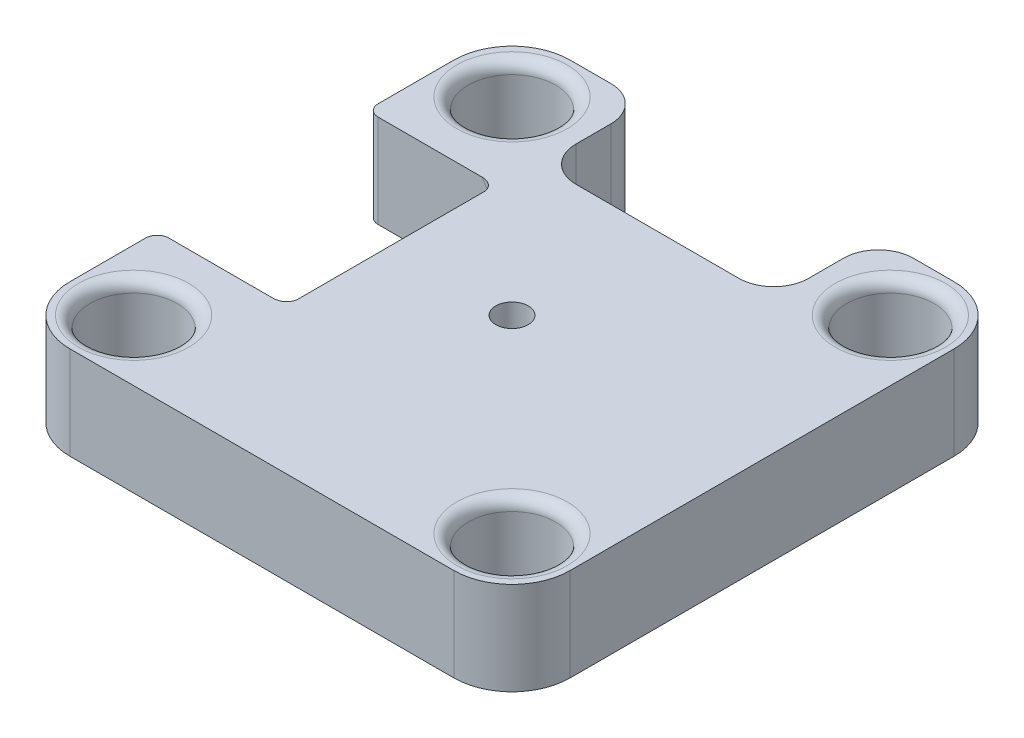
SolidWorks part; units mm, degrees
ref_plane "Front Plane" through (0, 0, 0) normal (0, 0, 1) x (1, 0, 0)
ref_plane "Top Plane" through (0, 0, 0) normal (0, 1, 0) x (1, 0, 0)
ref_plane "Right Plane" through (0, 0, 0) normal (1, 0, 0) x (0, 0, -1)
sketch "Sketch1" plane through (0, 0, 0) normal (0, 1, 0) x (1, 0, 0)
  line L0 (-20.6546, 20.6546) -> (0, 0) construction
  line L2 (27.305, -27.305) -> (-27.305, -27.305)
  line L3 (27.305, -27.305) -> (27.305, 27.305)
  line L4 (27.305, 27.305) -> (-27.305, 27.305)
  line L5 (-27.305, -27.305) -> (-27.305, 27.305)
  line L6 (27.305, -27.305) -> (-27.305, 27.305) construction
  line L7 (27.305, 27.305) -> (-27.305, -27.305) construction
  circle A0 centre (-20.6546, 20.6546) radius 4.7625
  circle A1 centre (20.6546, 20.6546) radius 4.7625
  circle A2 centre (20.6546, -20.6546) radius 4.7625
  circle A3 centre (-20.6546, -20.6546) radius 4.7625
  point P13 (0, 0)
  dimension "D3" = 9.525
  dimension "D1" = 45
  dimension "D2" = 29.21
  dimension "D5" = 54.61
  dimension "D4" = 4
extrude "Boss-Extrude1" add sketch "Sketch1" along normal mid plane 10.16
fillet "Fillet1" radius 6.35 4 edges at (-27.305, 0, -27.305) (27.305, 0, -27.305) (27.305, 0, 27.305) (-27.305, 0, 27.305)
fillet "Fillet2" radius 1.27 8 edges at (20.6546, 5.08, 25.4171) (20.6546, -5.08, 25.4171) (-20.6546, 5.08, 25.4171) (-20.6546, -5.08, 25.4171) (20.6546, -5.08, -15.8921) (20.6546, 5.08, -15.8921) (-20.6546, -5.08, -15.8921) (-20.6546, 5.08, -15.8921)
sketch "Sketch4" plane through (0, 0, 0) normal (0, 0, 1) x (1, 0, 0)
  line L0 (-27.305, 5.08) -> (-13.208, 5.08)
  line L1 (-20.955, 5.08) -> (20.955, 5.08) construction
  line L2 (-13.208, 5.08) -> (-8.128, -3.556)
  line L3 (-8.128, -3.556) -> (11.43, -3.556)
  line L4 (11.43, -3.556) -> (11.43, -5.08)
  line L5 (-20.955, -5.08) -> (20.955, -5.08) construction
  line L6 (11.43, -5.08) -> (-27.305, -5.08)
  line L7 (-27.305, -5.08) -> (-20.955, -5.08) construction
  line L8 (-27.305, -5.08) -> (-27.305, 5.08)
  dimension "D1" = 38.735
  dimension "D2" = 19.558
  dimension "D3" = 5.08
  dimension "D4" = 8.636
extrude "Cut-Extrude1" cut sketch "Sketch4" against normal mid plane 22.86
sketch "Sketch5" plane through (0, -3.556, 0) normal (0, -1, 0) x (1, 0, 0)
  line L1 (11.43, -11.43) -> (11.43, 11.43) construction
  circle A0 centre (0, 0) radius 1.778
  point P3 (11.43, 0)
  dimension "D1" = 3.556
extrude "Cut-Extrude2" cut sketch "Sketch5" against normal through all
fillet "Fillet3" radius 1.27 8 edges at (1.651, -3.556, -11.43) (1.651, -3.556, 11.43) (11.43, -3.556, 0) (-10.668, 0.762, -11.43) (-8.128, -3.556, 0) (-10.668, 0.762, 11.43) (-27.305, 0, -11.43) (-27.305, 0, 11.43)
sketch "Sketch6" plane through (0, 5.08, 0) normal (0, 1, 0) x (1, 0, 0)
  line L0 (20.955, 27.305) -> (-20.955, 27.305) construction
  line L1 (-12.7, 38.735) -> (12.7, 38.735)
  line L2 (-12.7, 38.735) -> (-12.7, 15.875)
  line L3 (-12.7, 15.875) -> (12.7, 15.875)
  line L4 (12.7, 38.735) -> (12.7, 15.875)
  line L5 (-12.7, 38.735) -> (12.7, 15.875) construction
  line L6 (-12.7, 15.875) -> (12.7, 38.735) construction
  point P0 (0, 27.305)
  dimension "D1" = 25.4
  dimension "D2" = 22.86
extrude "Cut-Extrude3" cut sketch "Sketch6" against normal through all
fillet "Fillet4" radius 3.81 4 edges at (12.7, 0, -27.305) (12.7, 0, -15.875) (-12.7, 0, -15.875) (-12.7, 0, -27.305)
